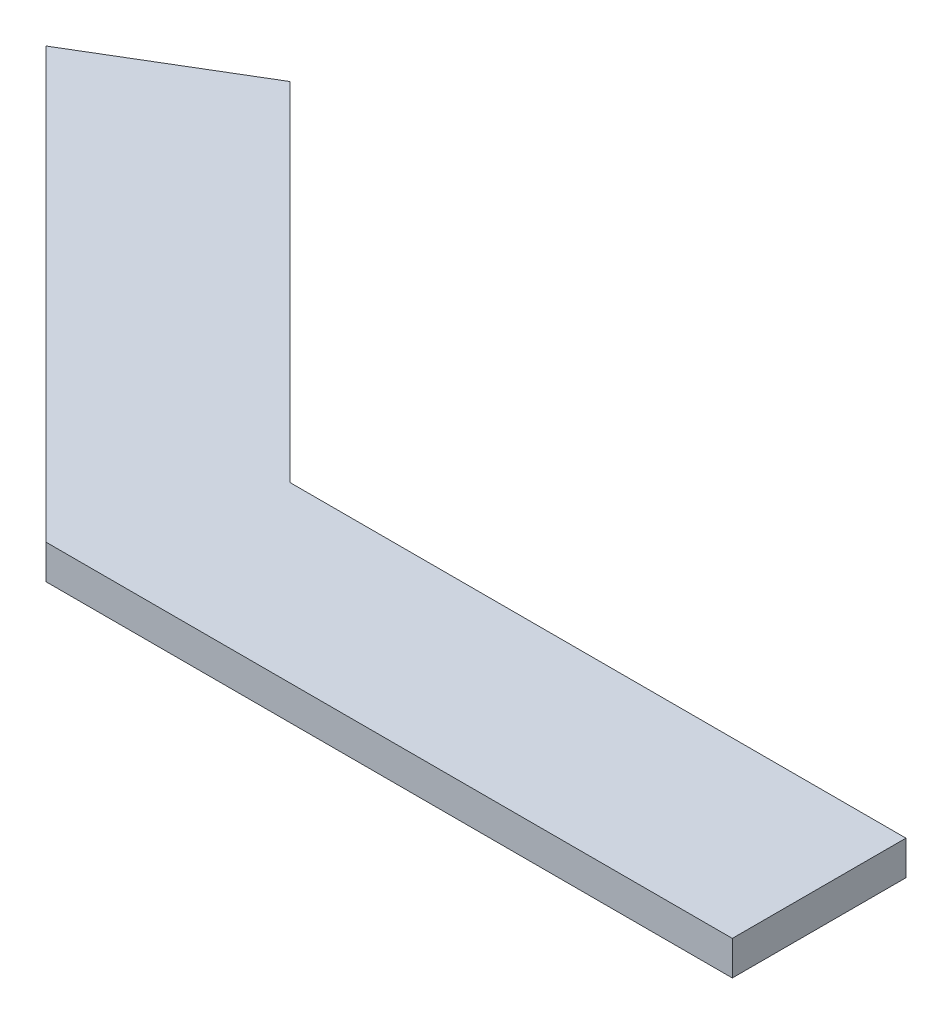
SolidWorks part; units mm, degrees
ref_plane "Front Plane" through (0, 0, 0) normal (0, 0, 1) x (1, 0, 0)
ref_plane "Top Plane" through (0, 0, 0) normal (0, 1, 0) x (1, 0, 0)
ref_plane "Right Plane" through (0, 0, 0) normal (1, 0, 0) x (0, 0, -1)
sketch "Sketch1" plane through (0, 0, 0) normal (0, 1, 0) x (1, 0, 0)
  line L1 (0, 0) -> (100, 0)
  line L2 (0, 0) -> (0, -100)
  line L3 (0, -100) -> (100, -100)
  line L4 (100, 0) -> (100, -100)
sketch "Sketch2" plane through (0, 5, 0) normal (0, 1, 0) x (1, 0, 0)
  line L0 (0, -100) -> (0, 0)
  line L1 (0, -100) -> (-62.614, -37.386)
  line L2 (-62.614, -37.386) -> (0, 0)
sketch "Sketch4" plane through (0, 0, 0) normal (0, -1, 0) x (1, 0, 0)
  line L0 (0, 100) -> (-62.614, 37.386)
  line L1 (-62.614, 37.386) -> (-58.321, 34.8227)
  line L2 (-58.321, 34.8227) -> (1.8562, 95)
  line L3 (100, 95) -> (-5, 95) construction
  line L4 (0, 100) -> (100, 100)
  line L5 (100, 100) -> (100, 95)
  line L6 (100, 95) -> (1.8562, 95)
sketch "Sketch5" plane through (0, -20.3, 0) normal (0, -1, 0) x (1, 0, 0)
  line L0 (0, 100) -> (-62.614, 37.386)
  line L1 (-62.614, 37.386) -> (-40.3455, 24.0898)
  line L2 (0, 100) -> (100, 100)
  line L3 (100, 100) -> (100, 74.7)
  line L4 (100, 74.7) -> (10.2648, 74.7)
  line L5 (-40.3455, 24.0898) -> (35.5648, 100) construction
  line L6 (100, 74.7) -> (-25.3, 74.7) construction
  line L7 (10.2648, 74.7) -> (-40.3455, 24.0898)
extrude "Boss-Extrude4" add sketch "Sketch5" along normal blind 5
